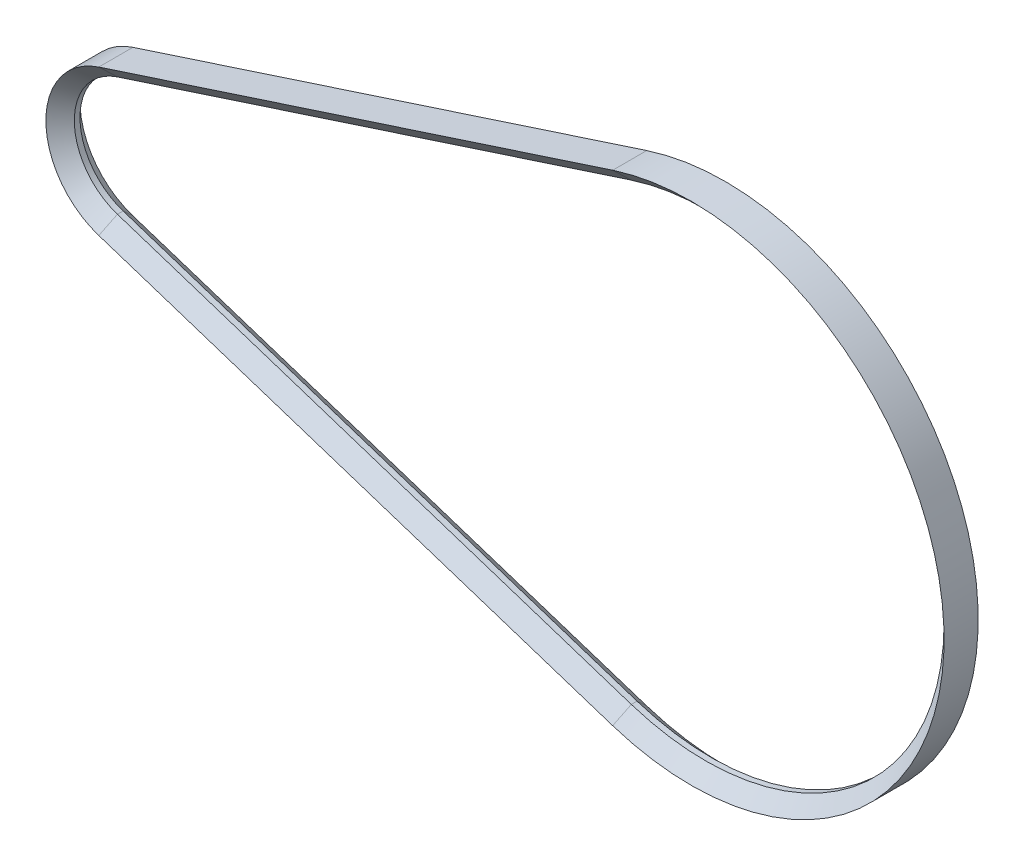
SolidWorks part; units mm, degrees
ref_plane "Face" through (0, 0, 0) normal (0, 0, 1) x (1, 0, 0)
ref_plane "Dessus" through (0, 0, 0) normal (0, 1, 0) x (1, 0, 0)
ref_plane "Droite" through (0, 0, 0) normal (1, 0, 0) x (0, 0, -1)
sketch "Esquisse1" plane through (0, 0, 0) normal (0, 0, 1) x (1, 0, 0)
  line L0 (86.98, 39.9309) -> (-3.41, 10.4581)
  line L1 (100, 0) -> (0, 0) construction
  line L2 (86.98, -39.9309) -> (-3.41, -10.4581)
  arc A0 (-3.41, 10.4581) -> (-3.41, -10.4581) centre (0, 0) ccw
  arc A1 (86.98, -39.9309) -> (86.98, 39.9309) centre (100, 0) ccw
  dimension "D2" = 11
  dimension "D3" = 42
  dimension "D1" = 100
sketch "Esquisse2" plane through (0, 0, 0) normal (0, 1, 0) x (1, 0, 0)
  line L0 (0, 0) -> (-35.5281, 0) construction
  line L1 (-13.5, -3) -> (-13.5, 3)
  line L2 (-13.5, 3) -> (-11, 0.5)
  line L3 (-13.5, -3) -> (-11, -0.5)
  line L4 (-11, 0.5) -> (-11, -0.5)
  point P6 (-13.5, 0)
  point P9 (-11, 0)
  dimension "D1" = 45
  dimension "D2" = 6
  dimension "D3" = 2.5
  dimension "D4" = 11
sweep "Balayage1" add profiles "Esquisse2" path "Esquisse1"
